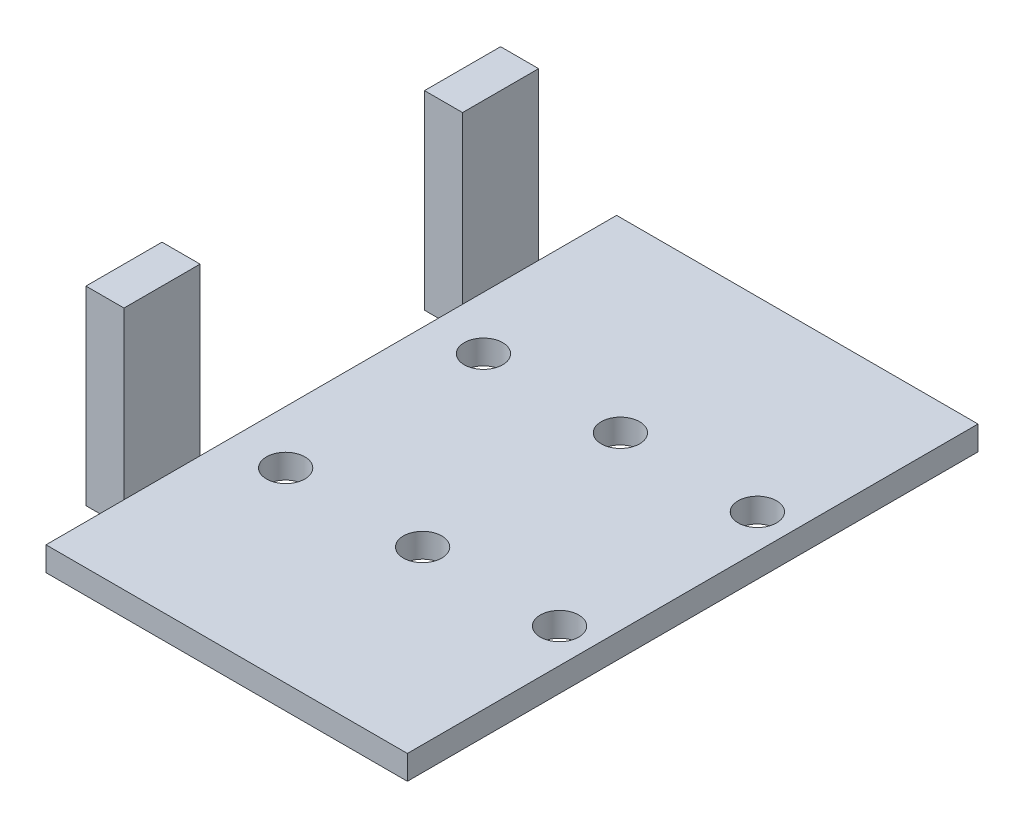
SolidWorks part; units mm, degrees
material "Plain Carbon Steel"
ref_plane "Front Plane" through (0, 0, 0) normal (0, 0, 1) x (1, 0, 0)
ref_plane "Top Plane" through (0, 0, 0) normal (0, 1, 0) x (1, 0, 0)
ref_plane "Right Plane" through (0, 0, 0) normal (1, 0, 0) x (0, 0, -1)
sketch "Sketch1" plane through (0, 0, 0) normal (0, 1, 0) x (1, 0, 0)
  line L0 (-120, -47.7) -> (-50, -47.7) construction
  line L1 (-36, 26) -> (36, 26) construction
  line L2 (-36, 26) -> (-36, -26) construction
  line L3 (-36, -26) -> (36, -26) construction
  line L4 (36, 26) -> (36, -26) construction
  line L5 (-36, 26) -> (36, -26) construction
  line L6 (-36, -26) -> (36, 26) construction
  line L7 (45, 75) -> (-50, 75)
  line L8 (45, 75) -> (45, -75)
  line L9 (45, -75) -> (-50, -75)
  line L10 (-120, 67.7) -> (-120, 47.7) construction
  line L11 (-50, -47.7) -> (-50, 47.7)
  line L12 (-50, 47.7) -> (-120, 47.7) construction
  line L13 (-120, -47.7) -> (-120, -67.7) construction
  line L14 (-120, 47.7) -> (-120, -47.7) construction
  line L15 (0, 0) -> (-120, 0) construction
  line L16 (-50, 75) -> (-50, 67.7)
  line L17 (-50, 67.7) -> (-120, 67.7) construction
  line L18 (-120, -67.7) -> (-50, -67.7) construction
  line L19 (-50, -67.7) -> (-50, -75)
  line L20 (-110, 57.7) -> (-110, -57.7) construction
  line L21 (-50, 67.7) -> (-50, 47.7)
  line L22 (-50, -47.7) -> (-50, -67.7)
  circle A0 centre (-36, 26) radius 5.05
  circle A1 centre (36, 26) radius 5.05
  circle A2 centre (36, -26) radius 5.05
  circle A3 centre (-36, -26) radius 5.05
  circle A4 centre (0, 26) radius 5.05
  circle A5 centre (0, -26) radius 5.05
  circle A6 centre (-110, 57.7) radius 2 construction
  circle A7 centre (-110, -57.7) radius 2 construction
  point P0 (0, 0)
  dimension "D3" = 10.1
  dimension "D12" = 4
  dimension "D1" = 52
  dimension "D2" = 72
  dimension "D4" = 45
  dimension "D5" = 75
  dimension "D6" = 75
  dimension "D7" = 95.4
  dimension "D8" = 20
  dimension "D9" = 50
  dimension "D10" = 120
  dimension "D11" = 10
  dimension "D13" = 10
  dimension "D14" = 10
extrude "Boss-Extrude1" add sketch "Sketch1" along normal blind 6.35
sketch "Sketch2" plane through (0, 0, 0) normal (0, 1, 0) x (1, 0, 0)
  line L0 (-50, 75) -> (-50, -75) construction
  line L1 (-50, 54.5) -> (-60, 54.5)
  line L2 (-50, 54.5) -> (-50, 34.5)
  line L3 (-50, 34.5) -> (-60, 34.5)
  line L4 (-60, 54.5) -> (-60, 34.5)
  line L5 (-60, 34.5) -> (-60, -34.5) construction
  line L6 (-50, -54.5) -> (-60, -54.5)
  line L7 (-50, -54.5) -> (-50, -34.5)
  line L8 (-50, -34.5) -> (-60, -34.5)
  line L9 (-60, -54.5) -> (-60, -34.5)
  line L10 (0, 0) -> (-60, 0) construction
  dimension "D1" = 10
  dimension "D2" = 69
  dimension "D3" = 20
  dimension "D4" = 20
extrude "Boss-Extrude2" add sketch "Sketch2" along normal blind 50
